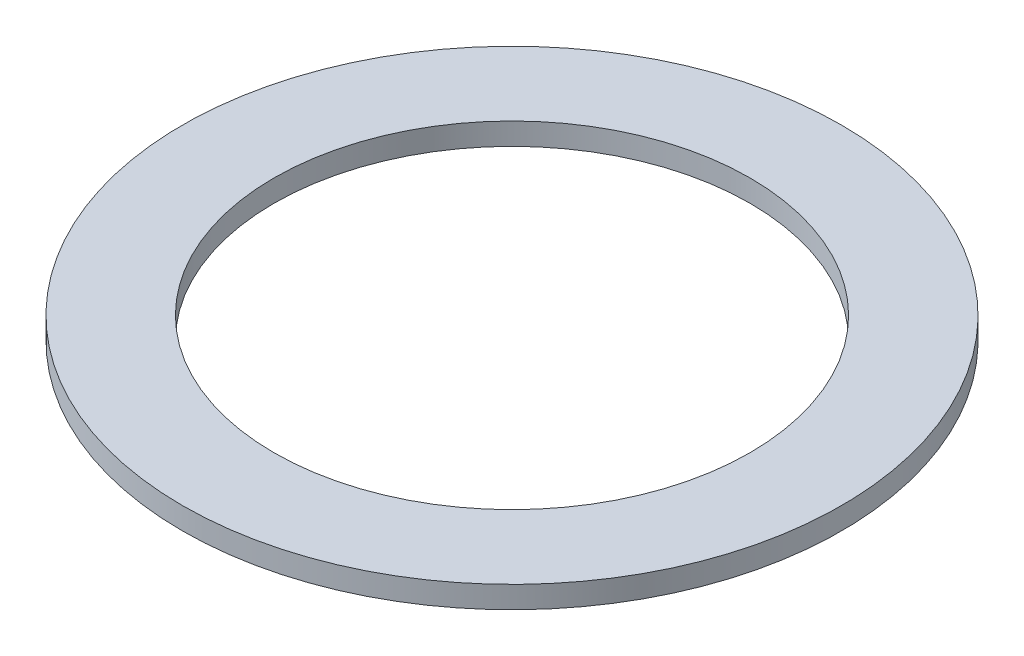
SolidWorks part; units mm, degrees
ref_plane "Front Plane" through (0, 0, 0) normal (0, 0, 1) x (1, 0, 0)
ref_plane "Top Plane" through (0, 0, 0) normal (0, 1, 0) x (1, 0, 0)
ref_plane "Right Plane" through (0, 0, 0) normal (1, 0, 0) x (0, 0, -1)
sketch "Sketch1" plane through (0, 0, 0) normal (0, 1, 0) x (1, 0, 0)
  circle A0 centre (0, 0) radius 32.5
  circle A1 centre (0, 0) radius 45
  dimension "D1" = 65
  dimension "D2" = 90
extrude "Boss-Extrude1" add sketch "Sketch1" along normal blind 3
